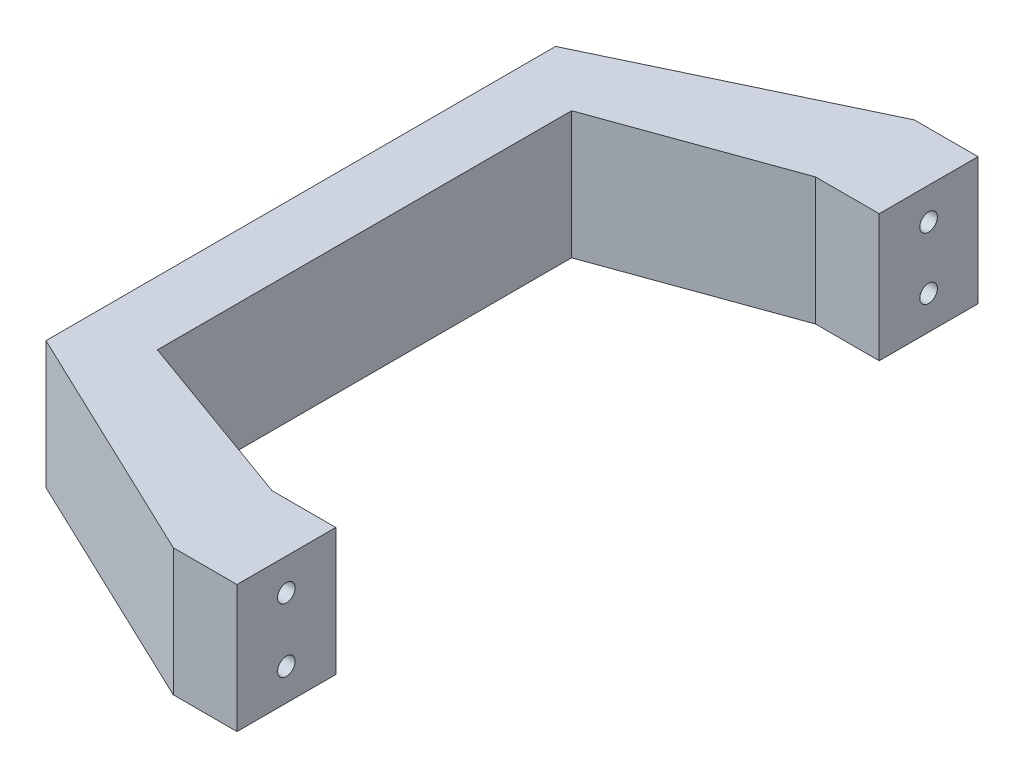
SolidWorks part; units mm, degrees
ref_plane "Front Plane" through (0, 0, 0) normal (0, 0, 1) x (1, 0, 0)
ref_plane "Top Plane" through (0, 0, 0) normal (0, 1, 0) x (1, 0, 0)
ref_plane "Right Plane" through (0, 0, 0) normal (1, 0, 0) x (0, 0, -1)
sketch "Sketch1" plane through (0, 0, 0) normal (0, 1, 0) x (1, 0, 0)
  line L0 (-370.2852, -60.7601) -> (-370.2852, -41.0652)
  line L3 (-382.9852, -169.1087) -> (-418.7317, -156.2253)
  line L4 (-370.2852, -41.0652) -> (-382.9852, -41.0652)
  line L5 (-382.9852, -41.0652) -> (-431.4317, -64.1344)
  line L6 (-370.2852, -60.7601) -> (-382.9852, -60.7601)
  line L7 (-382.9852, -60.7601) -> (-418.7317, -73.6435)
  line L8 (-418.7317, -73.6435) -> (-418.7317, -156.2253)
  line L12 (-431.4317, -165.7344) -> (-431.4317, -64.1344)
  line L13 (-370.2852, -169.1087) -> (-382.9852, -169.1087)
  line L14 (-370.2852, -169.1087) -> (-370.2852, -188.8036)
  line L15 (-370.2852, -188.8036) -> (-382.9852, -188.8036)
  line L16 (-382.9852, -188.8036) -> (-431.4317, -165.7344)
extrude "Boss-Extrude1" add sketch "Sketch1" along normal blind 25.4
sketch "Sketch2" plane through (-370.2852, 0, 0) normal (1, 0, 0) x (0, 0, -1)
  circle A0 centre (-178.9562, 19.05) radius 1.7526
  circle A1 centre (-178.9562, 6.35) radius 1.7526
  circle A2 centre (-50.9126, 6.7306) radius 1.7526
  circle A3 centre (-50.9126, 19.05) radius 1.7526
extrude "Cut-Extrude1" cut sketch "Sketch2" against normal blind 12.7
